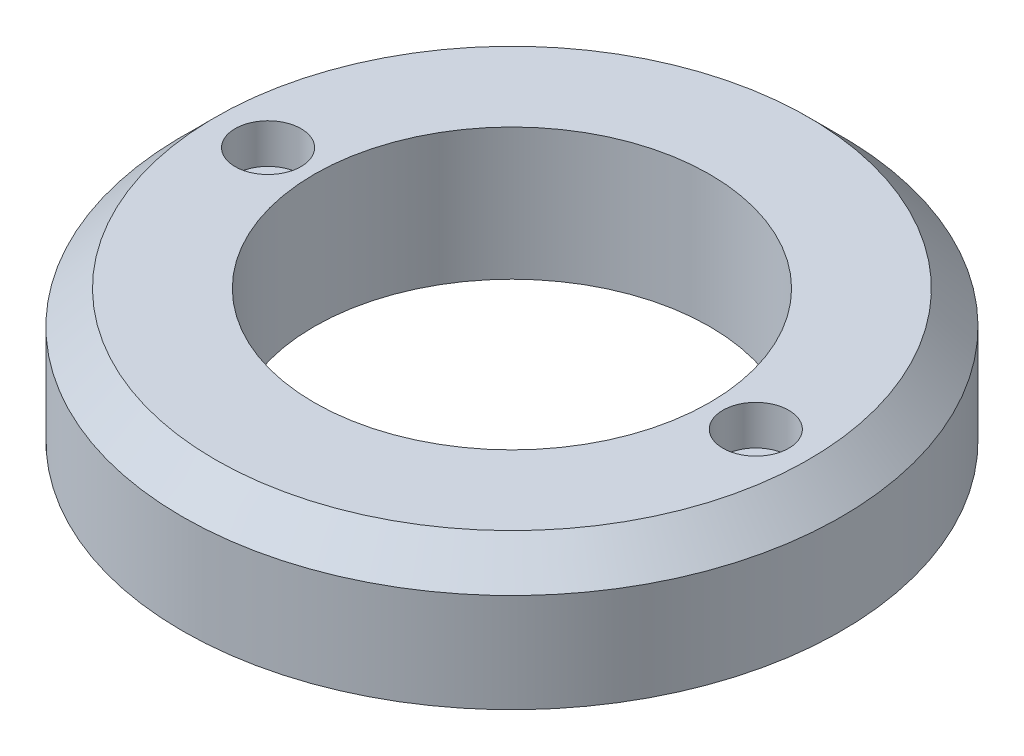
SolidWorks part; units mm, degrees
material "Malleable Cast Iron"
ref_plane "Front Plane" through (0, 0, 0) normal (0, 0, 1) x (1, 0, 0)
ref_plane "Top Plane" through (0, 0, 0) normal (0, 1, 0) x (1, 0, 0)
ref_plane "Right Plane" through (0, 0, 0) normal (1, 0, 0) x (0, 0, -1)
sketch "Sketch1" plane through (0, 0, 0) normal (0, 1, 0) x (1, 0, 0)
  circle A0 centre (0, 0) radius 50
  circle A1 centre (0, 0) radius 30
extrude "Boss-Extrude1" add sketch "Sketch1" along normal blind 20
chamfer "Chamfer1" distance 5 angle 45 1 edges at (0, 20, 50)
sketch "Sketch2" plane through (0, 20, 0) normal (0, 1, 0) x (1, 0, 0)
  point P3 (-37, 0)
  point P4 (0, 0)
  point P7 (37, 0)
  dimension "D1" = 2
hole_wizard "M6x1.0 Tapped Hole1" positions "3DSketch1" profile "Sketch3" tap size "M6x1.0" standard "ANSI Metric"
sketch3d "3DSketch1"
  point P0 (-37, 20, 0)
  point P3 (37, 20, 0)
sketch "Sketch3" plane through (-37, 20, 0) normal (1, 0, 0) x (0, 0, 1)
  line L0 (0, 0) -> (0, 51.5022)
  line L1 (0, 51.5022) -> (2.5, 50)
  line L2 (2.5, 50) -> (2.5, 0)
  line L5 (2.5, 0) -> (0, 0)
  line L10 (0, 51.5022) -> (-2.5, 50) construction
  line L11 (0, -6.35) -> (0, 107.95) construction
  dimension "Tap Drill Dia." = 5
  dimension "Tap Drill Depth" = 50
  dimension "Drill Angle" = 118
cosmetic thread "Hole Thread1"
cosmetic thread "Hole Thread2"
sketch "Sketch4" plane through (0, 20, 0) normal (0, 1, 0) x (1, 0, 0)
  circle A0 centre (-37, 0) radius 5
  circle A1 centre (37, 0) radius 5
extrude "Cut-Extrude1" cut sketch "Sketch4" against normal blind 6
